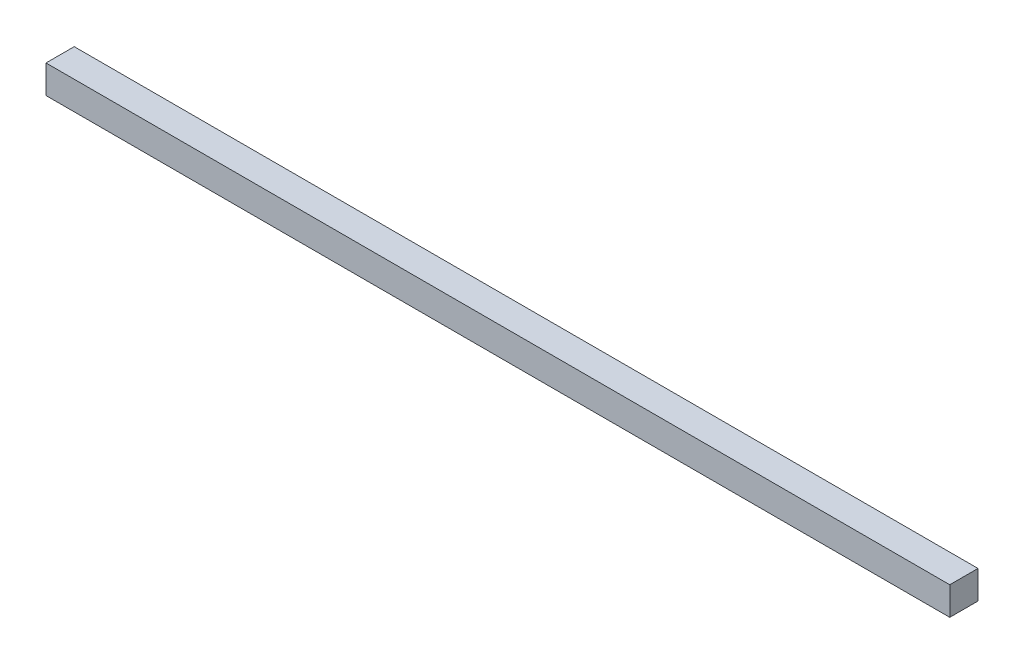
SolidWorks part; units mm, degrees
material "Pine"
ref_plane "Front Plane" through (0, 0, 0) normal (0, 0, 1) x (1, 0, 0)
ref_plane "Top Plane" through (0, 0, 0) normal (0, 1, 0) x (1, 0, 0)
ref_plane "Right Plane" through (0, 0, 0) normal (1, 0, 0) x (0, 0, -1)
sketch "Sketch1" plane through (0, 0, 0) normal (0, 0, 1) x (1, 0, 0)
  line L1 (-609.6, 19.05) -> (609.6, 19.05)
  line L2 (-609.6, 19.05) -> (-609.6, -19.05)
  line L3 (-609.6, -19.05) -> (609.6, -19.05)
  line L4 (609.6, 19.05) -> (609.6, -19.05)
  point P4 (0, 19.05)
  point P6 (609.6, 0)
  dimension "D1" = 1219.2
  dimension "D2" = 38.1
extrude "Boss-Extrude1" add sketch "Sketch1" along normal blind 38.1
